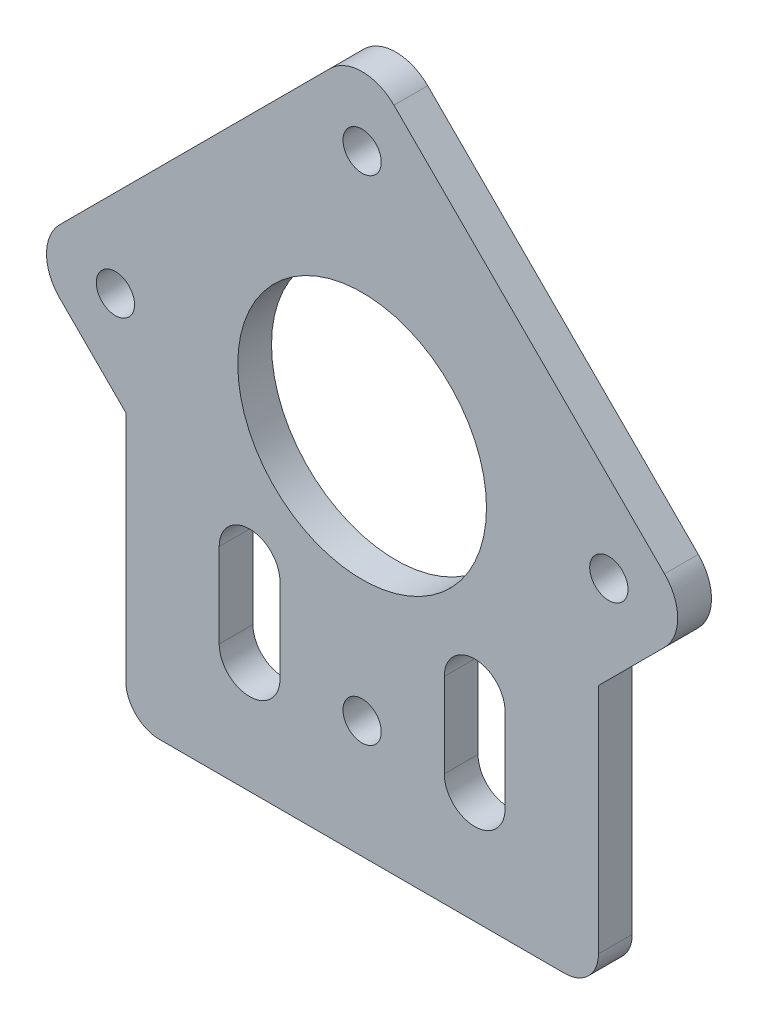
SolidWorks part; units mm, degrees
ref_plane "Ebene vorne" through (0, 0, 0) normal (0, 0, 1) x (1, 0, 0)
ref_plane "Ebene oben" through (0, 0, 0) normal (0, 1, 0) x (1, 0, 0)
ref_plane "Ebene rechts" through (0, 0, 0) normal (1, 0, 0) x (0, 0, -1)
sketch "Model" plane through (0, 0, 0) normal (0, 0, 1) x (1, 0, 0)
  line L0 (51, 3) -> (51, 23.6515)
  line L1 (51, 23.6515) -> (56.8701, 29.5216)
  line L2 (56.8701, 35.1784) -> (32.8284, 59.2201)
  line L3 (27.1716, 59.2201) -> (3.1299, 35.1784)
  line L4 (3.1299, 29.5216) -> (9, 23.6515)
  line L5 (9, 23.6515) -> (9, 3)
  line L6 (12, 0) -> (48, 0)
  line L7 (22.7, 10) -> (22.7, 17.5)
  line L8 (17.3, 17.5) -> (17.3, 10)
  line L9 (37.3, 10) -> (37.3, 17.5)
  line L10 (42.7, 17.5) -> (42.7, 10)
  circle A0 centre (30, 10.4297) radius 1.7
  circle A1 centre (51.9203, 32.35) radius 1.7
  circle A2 centre (30, 54.2703) radius 1.7
  circle A3 centre (8.0797, 32.35) radius 1.7
  circle A4 centre (30, 32.35) radius 11.05
  arc A5 (56.8701, 29.5216) -> (56.8701, 35.1784) centre (54.0416, 32.35) ccw
  arc A6 (32.8284, 59.2201) -> (27.1716, 59.2201) centre (30, 56.3916) ccw
  arc A7 (3.1299, 35.1784) -> (3.1299, 29.5216) centre (5.9584, 32.35) ccw
  arc A8 (9, 3) -> (12, 0) centre (12, 3) ccw
  arc A9 (48, 0) -> (51, 3) centre (48, 3) ccw
  arc A10 (22.7, 17.5) -> (17.3, 17.5) centre (20, 17.5) ccw
  arc A11 (17.3, 10) -> (22.7, 10) centre (20, 10) ccw
  arc A12 (42.7, 17.5) -> (37.3, 17.5) centre (40, 17.5) ccw
  arc A13 (37.3, 10) -> (42.7, 10) centre (40, 10) ccw
extrude "Aufsatz-Linear austragen1" add sketch "Model" along normal blind 3
